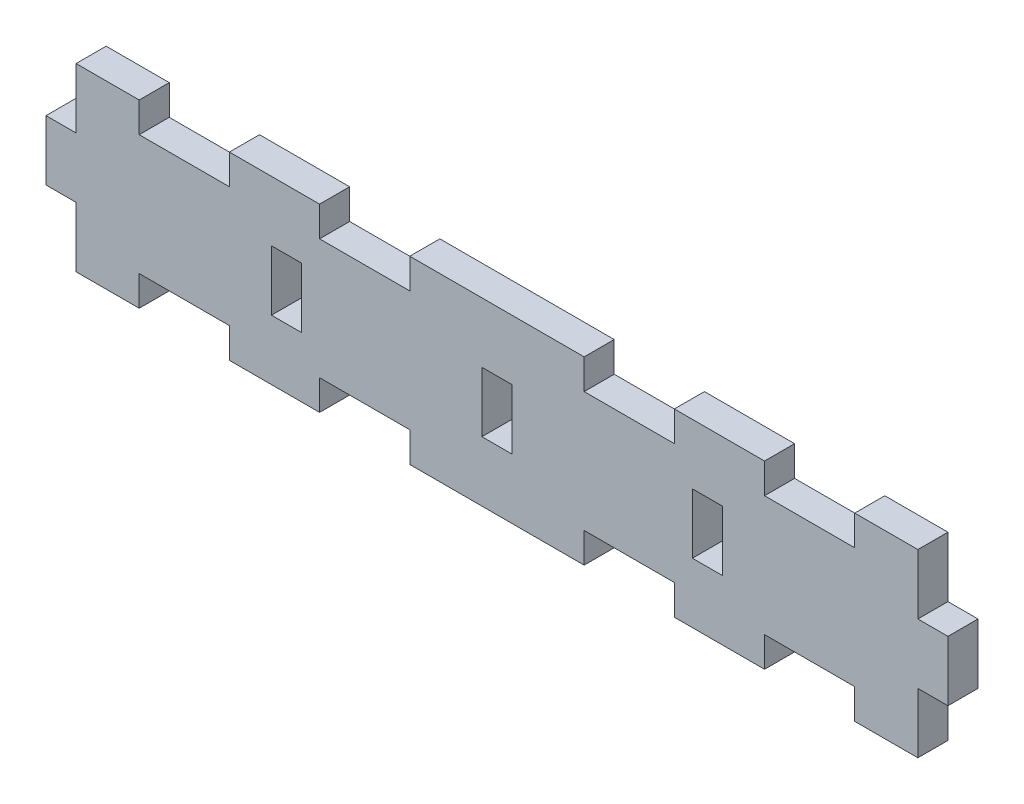
SolidWorks part; units mm, degrees
ref_plane "Front Plane" through (0, 0, 0) normal (0, 0, 1) x (1, 0, 0)
ref_plane "Top Plane" through (0, 0, 0) normal (0, 1, 0) x (1, 0, 0)
ref_plane "Right Plane" through (0, 0, 0) normal (1, 0, 0) x (0, 0, -1)
sketch "Sketch1" plane through (0, 0, 0) normal (0, 0, 1) x (1, 0, 0)
  line L0 (-106.8142, -27.999) -> (-38.0976, -27.999) construction
  line L1 (46.4024, -17.999) -> (46.4024, -22.999)
  line L2 (46.4024, -22.999) -> (51.4024, -22.999)
  line L3 (51.4024, -22.999) -> (51.4024, -32.999)
  line L4 (20.9024, -17.999) -> (35.9024, -17.999)
  line L5 (-9.0976, -17.999) -> (5.9024, -17.999)
  line L6 (-38.0976, -17.999) -> (-53.0976, -17.999)
  line L7 (-83.0976, -37.999) -> (-68.0976, -37.999)
  line L8 (-53.0976, -37.999) -> (-53.0976, -42.999)
  line L9 (-68.0976, -42.999) -> (-68.0976, -37.999)
  line L10 (-53.0976, -42.999) -> (-68.0976, -42.999)
  line L11 (-9.0976, -37.999) -> (-9.0976, -42.999)
  line L12 (-38.0976, -42.999) -> (-38.0976, -37.999)
  line L13 (-9.0976, -42.999) -> (-38.0976, -42.999)
  line L14 (20.9024, -37.999) -> (20.9024, -42.999)
  line L15 (5.9024, -42.999) -> (5.9024, -37.999)
  line L16 (20.9024, -42.999) -> (5.9024, -42.999)
  line L17 (46.4024, -37.999) -> (46.4024, -42.999)
  line L18 (35.9024, -42.999) -> (35.9024, -37.999)
  line L19 (46.4024, -42.999) -> (35.9024, -42.999)
  line L20 (-83.0976, -12.999) -> (-93.5976, -12.999)
  line L21 (-93.5976, -12.999) -> (-93.5976, -17.999)
  line L23 (-83.0976, -17.999) -> (-83.0976, -12.999)
  line L24 (46.4024, -12.999) -> (35.9024, -12.999)
  line L25 (35.9024, -12.999) -> (35.9024, -17.999)
  line L27 (46.4024, -17.999) -> (46.4024, -12.999)
  line L28 (20.9024, -12.999) -> (5.9024, -12.999)
  line L29 (5.9024, -12.999) -> (5.9024, -17.999)
  line L31 (20.9024, -17.999) -> (20.9024, -12.999)
  line L32 (-9.0976, -12.999) -> (-38.0976, -12.999)
  line L33 (-38.0976, -12.999) -> (-38.0976, -17.999)
  line L35 (-9.0976, -17.999) -> (-9.0976, -12.999)
  line L36 (-53.0976, -12.999) -> (-68.0976, -12.999)
  line L37 (-68.0976, -12.999) -> (-68.0976, -17.999)
  line L39 (-53.0976, -17.999) -> (-53.0976, -12.999)
  line L40 (-83.0976, -37.999) -> (-83.0976, -42.999)
  line L41 (-83.0976, -17.999) -> (-68.0976, -17.999)
  line L45 (-93.5976, -42.999) -> (-93.5976, -37.999)
  line L46 (-83.0976, -42.999) -> (-93.5976, -42.999)
  line L47 (-38.0976, -37.999) -> (-53.0976, -37.999)
  line L48 (-9.0976, -37.999) -> (5.9024, -37.999)
  line L49 (20.9024, -37.999) -> (35.9024, -37.999)
  line L50 (46.4024, -32.999) -> (51.4024, -32.999)
  line L51 (46.4024, -37.999) -> (46.4024, -32.999)
  line L52 (-23.5976, -12.999) -> (-23.5976, -2.4781) construction
  line L53 (-93.5976, -37.999) -> (-93.5976, -32.999)
  line L54 (-93.5976, -32.999) -> (-98.5976, -32.999)
  line L55 (-93.5976, -17.999) -> (-93.5976, -12.999)
  line L56 (-93.5976, -37.999) -> (-93.5976, -42.999)
  line L57 (-98.5976, -22.999) -> (-98.5976, -32.999)
  line L58 (-93.5976, -22.999) -> (-98.5976, -22.999)
  line L59 (-93.5976, -17.999) -> (-93.5976, -22.999)
  line L72 (13.9024, -32.999) -> (13.9024, -22.999)
  line L73 (13.9024, -22.999) -> (8.9024, -22.999)
  line L74 (8.9024, -22.999) -> (8.9024, -32.999)
  line L75 (8.9024, -32.999) -> (13.9024, -32.999)
  line L76 (-21.0976, -32.999) -> (-21.0976, -22.999)
  line L77 (-21.0976, -22.999) -> (-26.0976, -22.999)
  line L78 (-26.0976, -22.999) -> (-26.0976, -32.999)
  line L79 (-26.0976, -32.999) -> (-21.0976, -32.999)
  line L80 (-56.0976, -32.999) -> (-56.0976, -22.999)
  line L81 (-56.0976, -22.999) -> (-61.0976, -22.999)
  line L82 (-61.0976, -22.999) -> (-61.0976, -32.999)
  line L83 (-61.0976, -32.999) -> (-56.0976, -32.999)
  point P46 (51.4024, -27.999)
  point P53 (-98.5976, -27.999)
  dimension "D1" = 140
  dimension "D2" = 10
  dimension "D3" = 5
extrude "Boss-Extrude1" add sketch "Sketch1" along normal blind 5 contours L21 L59 L58 L57 L54 L53 L45 L46 L40 L7 L9 L10 L8 L47 L12 L13 L11 L48 L15 L16 L14 L49 L18 L19 L17 L51 L50 L3 L2 L1 L27 L24 L25 L4 L31 L28 L29 L5 L35 L32 L33 L6 L39 L36 L37 L41 L23 L20
